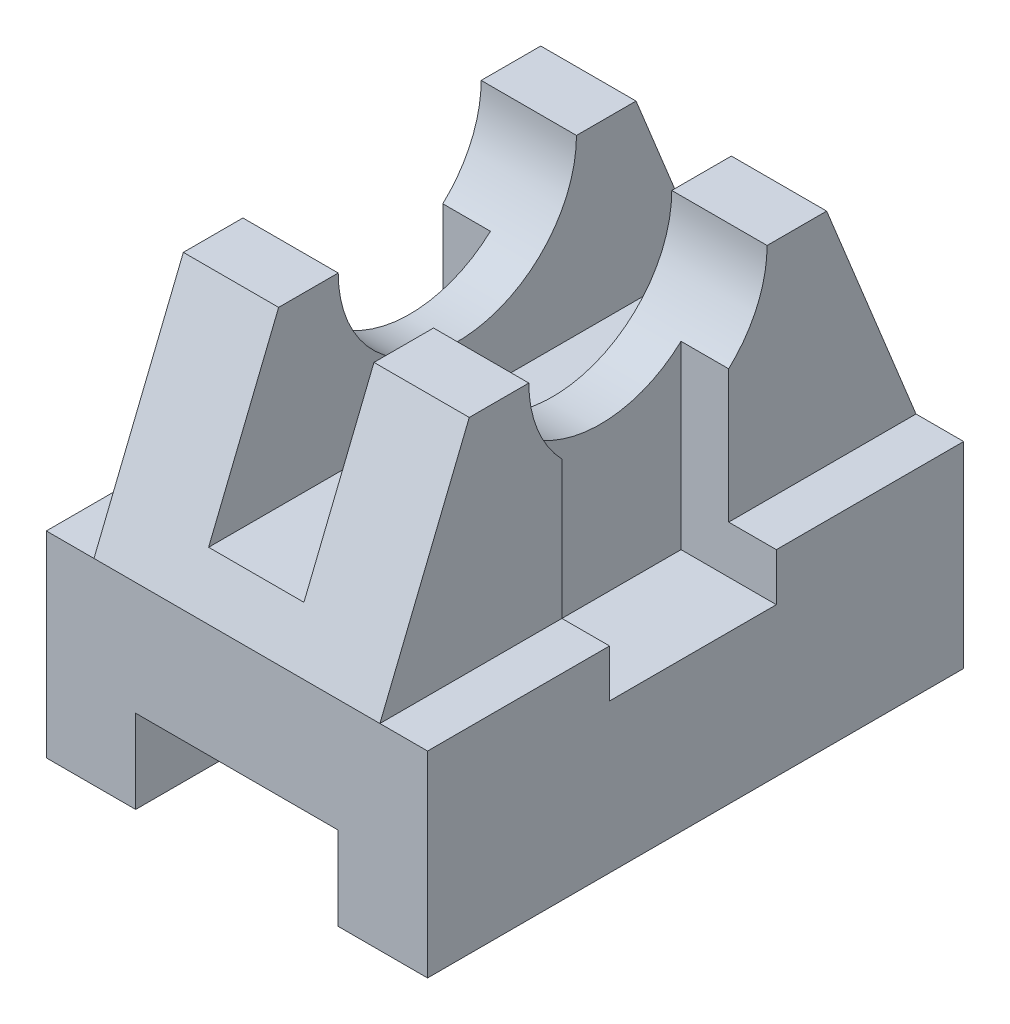
SolidWorks part; units mm, degrees
ref_plane "Front Plane" through (0, 0, 0) normal (0, 0, 1) x (1, 0, 0)
ref_plane "Top Plane" through (0, 0, 0) normal (0, 1, 0) x (1, 0, 0)
ref_plane "Right Plane" through (0, 0, 0) normal (1, 0, 0) x (0, 0, -1)
sketch "Sketch1" plane through (0, 0, 0) normal (0, 0, 1) x (1, 0, 0)
  line L0 (-48, 49.5) -> (-48, 0)
  line L1 (-48, 0) -> (-25.5, 0)
  line L2 (-25.5, 0) -> (-25.5, 21)
  line L3 (-25.5, 21) -> (25.5, 21)
  line L4 (25.5, 21) -> (25.5, 0)
  line L5 (25.5, 0) -> (48, 0)
  line L6 (48, 0) -> (48, 49.5)
  line L7 (48, 49.5) -> (-48, 49.5)
  point P2 (0, 21)
  dimension "D1" = 96
  dimension "D2" = 21
  dimension "D3" = 49.5
  dimension "D4" = 22.5
  dimension "D5" = 51
extrude "Boss-Extrude1" add sketch "Sketch1" against normal blind 135
sketch "Sketch2" plane through (0, 0, 0) normal (1, 0, 0) x (0, 0, -1)
  line L0 (135, 49.5) -> (0, 49.5) construction
  line L1 (37.5, 105) -> (22.5, 105)
  line L3 (97.5, 105) -> (112.5, 105)
  line L4 (22.5, 105) -> (0, 49.5)
  line L5 (0, 49.5) -> (135, 49.5)
  line L6 (135, 49.5) -> (112.5, 105)
  arc A0 (37.5, 105) -> (97.5, 105) centre (67.5, 105) ccw
  point P4 (67.5, 49.5)
  dimension "D1" = 60
  dimension "D2" = 15
  dimension "D3" = 55.5
extrude "Boss-Extrude2" add sketch "Sketch2" against normal blind 36 and the other way blind 36
sketch "Sketch3" plane through (0, 0, 0) normal (0, 0, 1) x (1, 0, 0)
  line L0 (36, 105) -> (-36, 105) construction
  line L1 (-12, 105) -> (12, 105)
  line L2 (-12, 105) -> (-12, 61.5)
  line L3 (-12, 61.5) -> (12, 61.5)
  line L4 (12, 105) -> (12, 61.5)
  line L5 (-12, 105) -> (12, 61.5) construction
  line L6 (-12, 61.5) -> (12, 105) construction
  line L7 (36, 49.5) -> (-36, 49.5) construction
  point P0 (0, 83.25)
  point P5 (0, 105)
  point P8 (0, 105)
  dimension "D1" = 24
  dimension "D2" = 12
extrude "Cut-Extrude1" cut sketch "Sketch3" against normal through all
sketch "Sketch4" plane through (0, 105, 0) normal (0, 1, 0) x (1, 0, 0)
  line L1 (24, 87.8287) -> (48, 87.8287)
  line L2 (24, 87.8287) -> (24, 45.8287)
  line L3 (24, 45.8287) -> (48, 45.8287)
  line L4 (48, 87.8287) -> (48, 45.8287)
  line L5 (24, 87.8287) -> (48, 45.8287) construction
  line L6 (24, 45.8287) -> (48, 87.8287) construction
  line L7 (48, 135) -> (48, 0) construction
  line L9 (12, 97.5) -> (12, 37.5) construction
  point P0 (35.6164, 67.5)
  point P13 (12, 67.5)
  dimension "D1" = 42
  dimension "D2" = 24
extrude "Cut-Extrude2" cut sketch "Sketch4" against normal blind 67.5
mirror "Mirror1" about plane through (0, 0, 0) normal (1, 0, 0) of "Cut-Extrude2"
